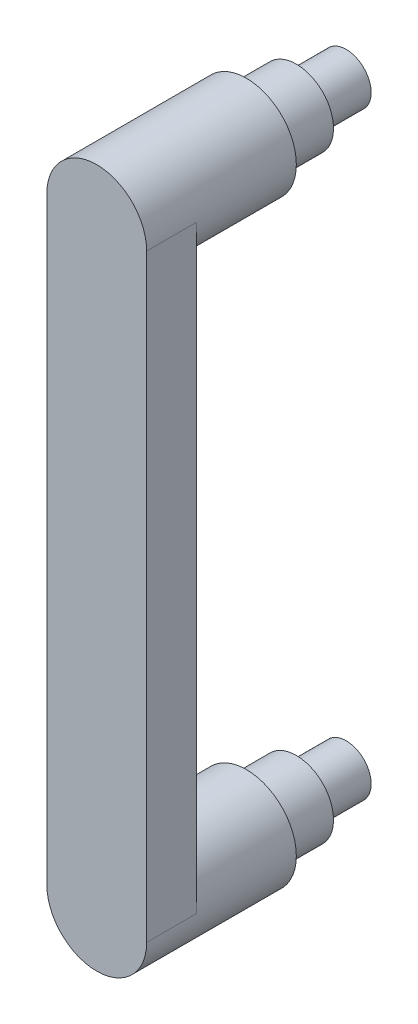
SolidWorks part; units mm, degrees
ref_plane "前视基准面" through (0, 0, 0) normal (0, 0, 1) x (1, 0, 0)
ref_plane "上视基准面" through (0, 0, 0) normal (0, 1, 0) x (1, 0, 0)
ref_plane "右视基准面" through (0, 0, 0) normal (1, 0, 0) x (0, 0, -1)
sketch "草图1" plane through (0, 0, 0) normal (0, 0, 1) x (1, 0, 0)
  circle A0 centre (0, 0) radius 1.49
  dimension "D1" = 2.98
extrude "凸台-拉伸1" add sketch "草图1" along normal blind 4
sketch "草图2" plane through (0, 0, 0) normal (0, 0, -1) x (-1, 0, 0)
  circle A0 centre (0, 0) radius 2
  dimension "D1" = 4
extrude "凸台-拉伸2" add sketch "草图2" along normal blind 4
sketch "草图3" plane through (0, 0, 4) normal (0, 0, 1) x (1, 0, 0)
  circle A0 centre (0, 0) radius 2
  dimension "D1" = 4
extrude "凸台-拉伸3" add sketch "草图3" along normal blind 4
sketch "草图4" plane through (0, 0, 0) normal (0, 1, 0) x (1, 0, 0)
  line L0 (2, 4) -> (-2, 4) construction
  line L1 (-2, 4) -> (2, 4)
  line L2 (-2, 4) -> (-2, 6)
  line L3 (-2, 6) -> (2, 6)
  line L4 (2, 4) -> (2, 6)
  point P5 (1.2674, 4)
  point P9 (-1.49, 6.4821)
  dimension "D1" = 2
extrude "凸台-拉伸4" add sketch "草图4" along normal blind 12 and the other way up to surface other way up to face at (-2, 0, -4)
sketch "草图6" plane through (0, 0, 0) normal (0, 1, 0) x (1, 0, 0)
  line L1 (-2, -8) -> (2, -8)
  line L2 (-2, -8) -> (-2, -10)
  line L3 (-2, -10) -> (2, -10)
  line L4 (2, -8) -> (2, -10)
  point P5 (2, -8)
  dimension "D1" = 2
extrude "凸台-拉伸5" add sketch "草图6" along normal blind 12 and the other way up to surface other way up to face at (2, 0, 8)
ref_plane "基准面4" through (0, 12, 0) normal (0, 1, 0) x (1, 0, 0)
mirror "镜向2" about plane through (0, 12, 0) normal (0, 1, 0) of bodies 105
sketch "草图7" plane through (0, 0, 0) normal (1, 0, 0) x (0, 0, -1)
  line L5 (-10, 26) -> (6, 26) construction
  line L6 (6, -2) -> (6, 0) construction
  line L7 (-2, 26) -> (6, 26)
  line L8 (-2, 26) -> (-2, -2)
  line L9 (-2, -2) -> (6, -2)
  line L10 (6, 26) -> (6, -2)
extrude "切除-拉伸1" cut sketch "草图7" against normal blind 12 and the other way blind 12
sketch "草图8" plane through (0, 0, 2) normal (0, 0, -1) x (-1, 0, 0)
  circle A0 centre (0, 24) radius 1
  circle A1 centre (0, 0) radius 1
  dimension "D1" = 2
  dimension "D2" = 2
extrude "凸台-拉伸6" add sketch "草图8" along normal blind 2
